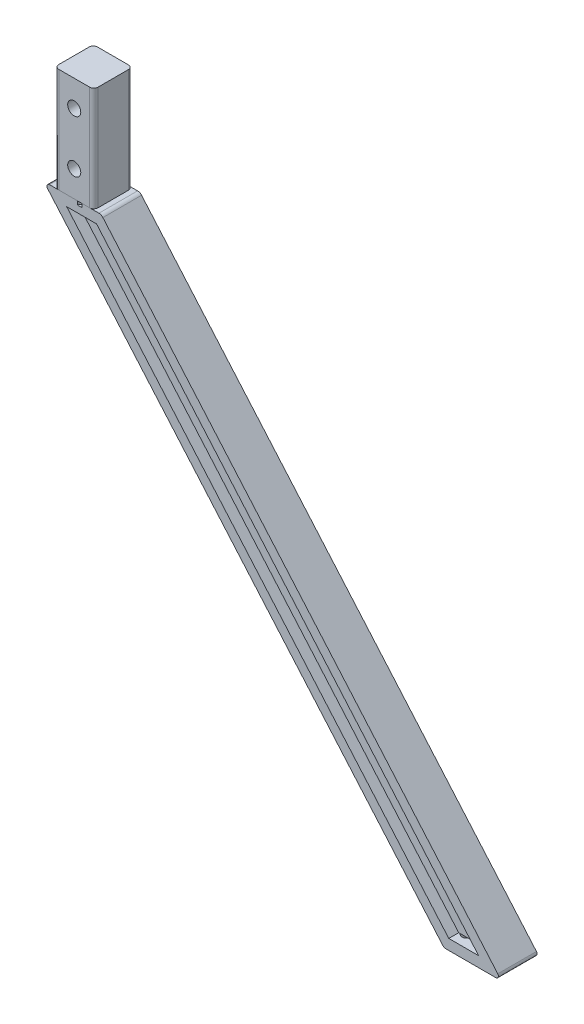
SolidWorks part; units mm, degrees
material "6061-T6 (SS)"
ref_plane "Front Plane" through (0, 0, 0) normal (0, 0, 1) x (1, 0, 0)
ref_plane "Top Plane" through (0, 0, 0) normal (0, 1, 0) x (1, 0, 0)
ref_plane "Right Plane" through (0, 0, 0) normal (1, 0, 0) x (0, 0, -1)
sketch "Sketch1" plane through (0, 0, 0) normal (0, 0, 1) x (1, 0, 0)
  line L0 (-0.7599, 0.8803) -> (-192.6595, 223.1982)
  line L1 (1.1629, 0) -> (25.1661, 0)
  line L2 (26.1275, 2.0998) -> (-165.7722, 224.4177)
  line L3 (-167.6949, 225.298) -> (-191.6981, 225.298)
  arc A0 (-192.6595, 223.1982) -> (-191.6981, 225.298) centre (-191.6981, 224.028) cw
  arc A1 (-165.7722, 224.4177) -> (-167.6949, 225.298) centre (-167.6949, 222.758) ccw
  arc A2 (25.1661, 0) -> (26.1275, 2.0998) centre (25.1661, 1.27) ccw
  arc A3 (1.1629, 0) -> (-0.7599, 0.8803) centre (1.1629, 2.54) cw
  point P7 (-194.472, 225.298)
  point P12 (27.94, 0)
  point P15 (0, 0)
  dimension "D4" = 2.54
  dimension "D5" = 1.27
  dimension "D6" = 1.27
  dimension "D7" = 2.54
  dimension "D1" = 225.298
  dimension "D2" = 27.94
  dimension "D3" = 49.2
extrude "Boss-Extrude1" add sketch "Sketch1" along normal blind 18.796
sketch "Sketch3" plane through (0, 0, 18.796) normal (0, 0, 1) x (1, 0, 0)
  line L0 (0, 0) -> (27.94, 0)
  line L5 (2.6445, 5.08) -> (18.1814, 5.08)
  line L8 (27.94, 0) -> (-132.1274, 228.6) construction
  line L9 (-132.1274, 228.6) -> (-160.0674, 228.6) construction
  line L10 (-160.0674, 228.6) -> (0, 0) construction
  line L11 (-150.3089, 223.52) -> (2.6445, 5.08) construction
  line L12 (18.1814, 5.08) -> (-134.7719, 223.52) construction
  line L13 (-134.7719, 223.52) -> (-150.3089, 223.52) construction
  line L31 (-183.3763, 220.218) -> (2.3258, 5.08)
  line L32 (2.3258, 5.08) -> (16.8443, 5.08)
  line L33 (16.8443, 5.08) -> (-168.8578, 220.218)
  line L34 (-168.8578, 220.218) -> (-183.3763, 220.218)
  line L35 (-183.3763, 220.218) -> (2.3258, 5.08)
  line L36 (2.3258, 5.08) -> (16.8443, 5.08)
  line L37 (16.8443, 5.08) -> (-168.8578, 220.218)
  line L38 (-168.8578, 220.218) -> (-183.3763, 220.218)
  dimension "D1" = 5.08
  dimension "D2" = 5.08
extrude "Cut-Extrude1" cut sketch "Sketch3" against normal blind 4.826
sketch "Sketch4" plane through (0, 0, 0) normal (0, 0, -1) x (-1, 0, 0)
  line L0 (-27.94, 0) -> (0, 0)
  line L7 (-18.1814, 5.08) -> (-2.6445, 5.08)
  line L8 (0, 0) -> (160.0674, 228.6) construction
  line L9 (160.0674, 228.6) -> (132.1274, 228.6) construction
  line L10 (132.1274, 228.6) -> (-27.94, 0) construction
  line L11 (-2.6445, 5.08) -> (150.3089, 223.52) construction
  line L12 (150.3089, 223.52) -> (134.7719, 223.52) construction
  line L13 (134.7719, 223.52) -> (-18.1814, 5.08) construction
  line L30 (183.3763, 220.218) -> (168.8578, 220.218)
  line L31 (168.8578, 220.218) -> (-16.8443, 5.08)
  line L32 (-16.8443, 5.08) -> (-2.3258, 5.08)
  line L33 (-2.3258, 5.08) -> (183.3763, 220.218)
  line L34 (183.3763, 220.218) -> (168.8578, 220.218)
  line L35 (168.8578, 220.218) -> (-16.8443, 5.08)
  line L36 (-16.8443, 5.08) -> (-2.3258, 5.08)
  line L37 (-2.3258, 5.08) -> (183.3763, 220.218)
  dimension "D1" = 5.08
  dimension "D2" = 5.08
extrude "Cut-Extrude2" cut sketch "Sketch4" against normal blind 4.826
sketch "Sketch5" plane through (0, 223.52, 0) normal (0, -1, 0) x (1, 0, 0)
  line L0 (-150.3089, 0) -> (-134.7719, 0) construction
  line L1 (-192.6595, 9.398) -> (26.4361, 9.398) construction
  line L2 (-192.6595, 18.796) -> (-192.6595, 0) construction
  line L3 (26.4361, 0) -> (26.4361, 18.796) construction
  circle A0 centre (-176.9482, 0) radius 1.143
  circle A1 centre (-176.9482, 18.796) radius 1.143
  dimension "D2" = 2.286
  dimension "D1" = 11.176
extrude "Cut-Extrude3" cut sketch "Sketch5" against normal through all
sketch "Sketch6" plane through (0, 5.08, 0) normal (0, 1, 0) x (1, 0, 0)
  line L1 (2.6445, -12.7) -> (18.1814, -12.7) construction
  line L2 (26.4361, -9.398) -> (-191.6981, -9.398) construction
  line L3 (26.4361, -18.796) -> (26.4361, 0) construction
  line L4 (-191.6981, -18.796) -> (-191.6981, 0) construction
  circle A1 centre (4.9931, -12.7) radius 2.286
  circle A2 centre (4.9931, -6.096) radius 2.286
  dimension "D1" = 8.382
  dimension "D2" = 4.572
extrude "Cut-Extrude4" cut sketch "Sketch6" against normal through all
sketch "Sketch9" plane through (0, 225.298, 0) normal (0, 1, 0) x (1, 0, 0)
  line L5 (-187.1895, 0) -> (-172.2035, 0)
  line L6 (-189.2215, -2.032) -> (-189.2215, -16.764)
  line L7 (-187.1895, -18.796) -> (-172.2035, -18.796)
  line L8 (-170.1715, -2.032) -> (-170.1715, -16.764)
  arc A0 (-170.1715, -2.032) -> (-172.2035, 0) centre (-172.2035, -2.032) ccw
  arc A1 (-172.2035, -18.796) -> (-170.1715, -16.764) centre (-172.2035, -16.764) ccw
  arc A2 (-189.2215, -16.764) -> (-187.1895, -18.796) centre (-187.1895, -16.764) ccw
  arc A3 (-189.2215, -2.032) -> (-187.1895, 0) centre (-187.1895, -2.032) cw
  point P12 (-170.1715, -18.796)
  point P15 (-189.2215, -18.796)
  point P18 (-189.2215, 0)
  dimension "D3" = 2.032
  dimension "D1" = 18.796
  dimension "D2" = 19.05
extrude "Boss-Extrude2" add sketch "Sketch9" along normal blind 50.8 separate body
sketch "Sketch10" plane through (0, 0, 18.796) normal (0, 0, 1) x (1, 0, 0)
  line L2 (-178.0912, 225.298) -> (-191.6981, 225.298) construction
  line L4 (-187.1895, 276.098) -> (-172.2035, 276.098) construction
  line L5 (-187.1895, 225.298) -> (-172.2035, 225.298) construction
  circle A0 centre (-179.6965, 237.998) radius 3.175
  circle A1 centre (-179.6965, 263.398) radius 3.175
  point P4 (-182.8715, 237.998)
  point P7 (-179.6965, 276.098)
  point P10 (0, 0)
  dimension "D1" = 6.35
  dimension "D3" = 6.35
  dimension "D2" = 12.7
  dimension "D4" = 38.1
extrude "Cut-Extrude5" cut sketch "Sketch10" against normal through all both and the other way through all
